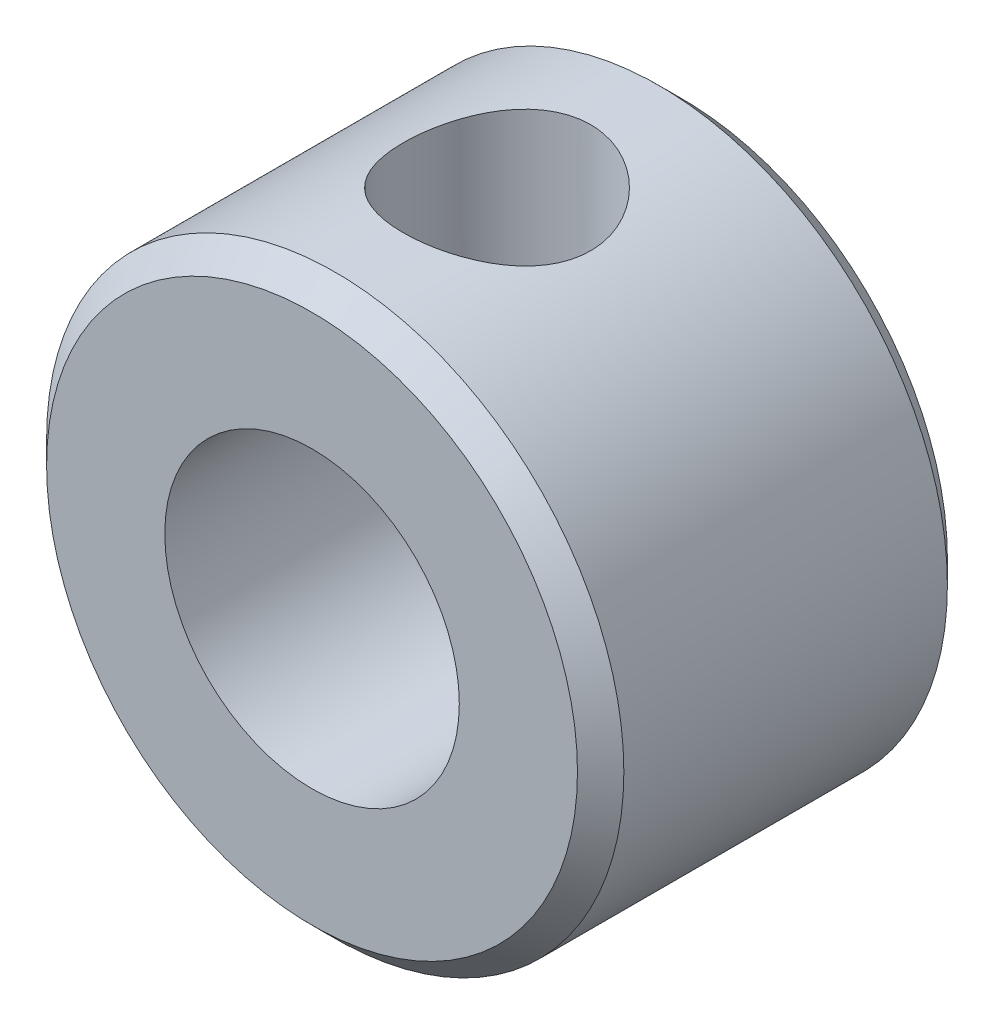
SolidWorks part; units mm, degrees
ref_plane "Front" through (0, 0, 0) normal (0, 0, 1) x (1, 0, 0)
ref_plane "Top" through (0, 0, 0) normal (0, 1, 0) x (1, 0, 0)
ref_plane "Right" through (0, 0, 0) normal (1, 0, 0) x (0, 0, -1)
sketch "Sketch1" plane through (0, 0, 0) normal (0, 0, 1) x (1, 0, 0)
  circle A0 centre (0, 0) radius 3.175
  circle A1 centre (0, 0) radius 6.223
  dimension "D1" = 6.35
  dimension "D2" = 12.446
sketch "Sketch2" plane through (0, 0, 0) normal (0, 1, 0) x (1, 0, 0)
  line L0 (0, -3.9878) -> (0, 3.9878)
  point P3 (0, 0)
sweep "Sweep1" add profiles "Sketch1" path "Sketch2"
chamfer "Chamfer1" distance 0.5 angle 45 2 edges at (6.223, 0, -3.9878) (6.223, 0, 3.9878)
hole_wizard "Tap Drill for #10-32 Tap1" positions "Sketch3" profile "Sketch4" hole size "#10-32" standard "ANSI Inch"
sketch "Sketch3" plane through (0, 0, 0) normal (0, 1, 0) x (1, 0, 0)
  point P0 (0, 0)
sketch "Sketch4" plane through (0, 0, 0) normal (1, 0, 0) x (0, 0, -1)
  line L0 (0, 0) -> (0, 6.223)
  line L1 (0, 6.223) -> (2.0193, 6.223)
  line L2 (2.0193, 6.223) -> (2.0193, 0)
  line L5 (2.0193, 0) -> (0, 0)
  line L11 (0, -6.35) -> (0, 107.95) construction
  dimension "Thru Hole Dia." = 4.0386
  dimension "Thru Hole Depth" = 6.223
